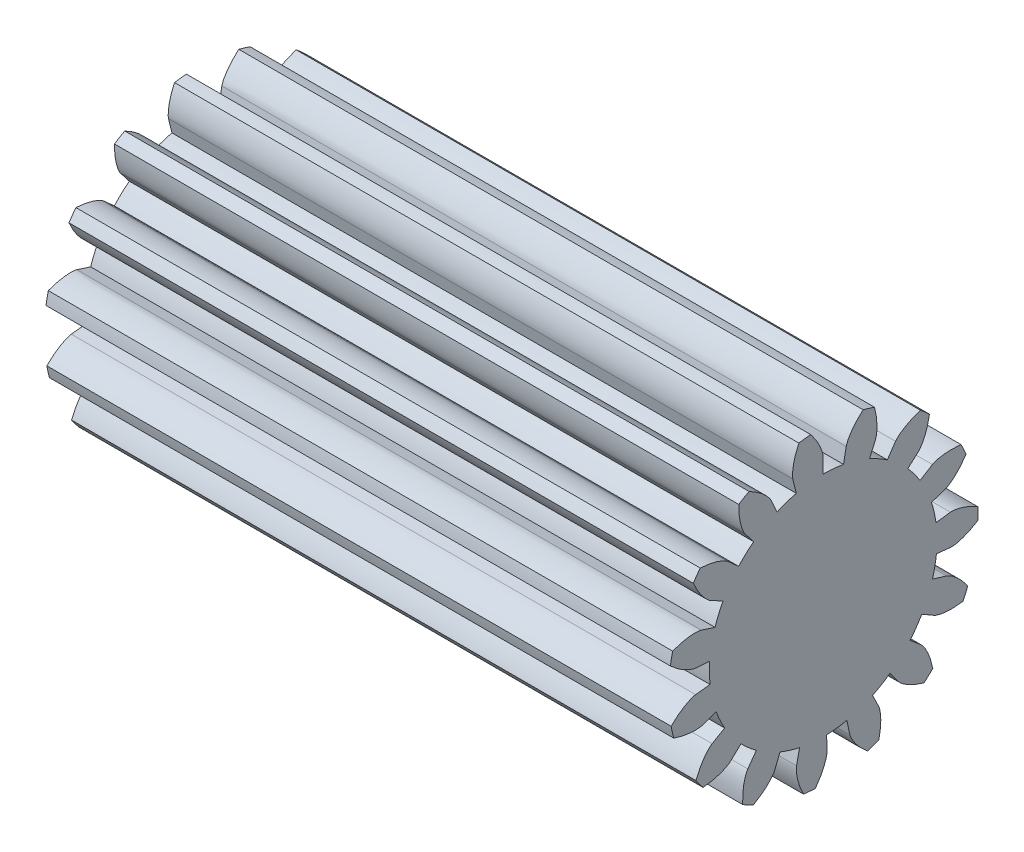
SolidWorks part; units mm, degrees
ref_plane "Front Plane" through (0, 0, 0) normal (1, 0, 0) x (0, 1, 0)
ref_plane "Top Plane" through (0, 0, 0) normal (0, 0, 1) x (0, 1, 0)
ref_plane "Right Plane" through (0, 0, 0) normal (0, 1, 0) x (-1, 0, 0)
sketch "Sketch1" plane through (0, 0, 0) normal (1, 0, 0) x (0, 1, 0)
  circle A0 centre (0, 0) radius 2.8333
  circle A1 centre (0, 0) radius 2.3492 construction
  circle A2 centre (0, 0) radius 2.0833 construction
  circle A3 centre (0, 0) radius 2.5 construction
  dimension "D1" = 5.6667
  dimension "D2" = 4.6985
  dimension "D3" = 4.1667
  dimension "D4" = 5
extrude "Boss-Extrude1" add sketch "Sketch1" along normal blind 11.43
sketch "Sketch3" plane through (11.43, 0, 0) normal (1, 0, 0) x (0, 1, 0)
  line L0 (0, 0) -> (2.3492, 0) construction
  line L1 (0, 0) -> (2.4997, 0.0373) construction
  line L2 (0, 0) -> (2.4899, -0.2242) construction
  line L3 (2.4899, -0.2242) -> (2.3398, -0.2107)
  line L4 (2.4899, -0.2242) -> (3.2461, -0.2923)
  line L5 (3.2461, 0.7075) -> (3.2461, -0.2923)
  line L6 (2.3492, 0) -> (2.0833, 0)
  line L7 (2.3398, -0.2107) -> (2.0749, -0.1869)
  circle A0 centre (0, 0) radius 2.5 construction
  circle A1 centre (0, 0) radius 2.3492 construction
  circle A2 centre (0, 0) radius 2.0833 construction
  arc A3 (2.0833, 0) -> (2.0749, -0.1869) centre (0, 0) cw
  spline S0 degree 4 poles (2.3492, 0) (2.351, 0) (2.3558, 0.0003) (2.3708, 0.0017) (2.4002, 0.0065) (2.436, 0.0154) (2.4766, 0.0283) (2.5151, 0.043) (2.5477, 0.0568) (2.5797, 0.0719) (2.6112, 0.0879) (2.6488, 0.1086) (2.6932, 0.1351) (2.7439, 0.1686) (2.7998, 0.2094) (2.8551, 0.254) (2.908, 0.3003) (2.9597, 0.3497) (3.0083, 0.3994) (3.0568, 0.4536) (3.1005, 0.5049) (3.1472, 0.5652) (3.1841, 0.6146) (3.2302, 0.6825) (3.2566, 0.7234) (3.2865, 0.7723) (3.2993, 0.7944) (3.3072, 0.808) knots 0 0 0 0 0 0.005377 0.015084 0.04661 0.092111 0.119476 0.146842 0.174209 0.201575 0.228941 0.256307 0.307035 0.361767 0.4165 0.471232 0.525964 0.580697 0.635429 0.690161 0.744894 0.799626 0.854358 0.909091 0.954545 1 1 1 1 1 construction
  spline S1 degree 4 poles (2.3492, 0) (2.351, 0) (2.3558, 0.0003) (2.3708, 0.0017) (2.4002, 0.0065) (2.436, 0.0154) (2.4766, 0.0283) (2.5151, 0.043) (2.5477, 0.0568) (2.5797, 0.0719) (2.6112, 0.0879) (2.6488, 0.1086) (2.6932, 0.1351) (2.7439, 0.1686) (2.7998, 0.2094) (2.8551, 0.254) (2.908, 0.3003) (2.9597, 0.3497) (3.0083, 0.3994) (3.0568, 0.4536) (3.1005, 0.5049) (3.1472, 0.5652) (3.1841, 0.6146) (3.2202, 0.6678) (3.2374, 0.694) (3.2461, 0.7075) knots 0 0 0 0 0 0.005377 0.015084 0.04661 0.092111 0.119476 0.146842 0.174209 0.201575 0.228941 0.256307 0.307035 0.361767 0.4165 0.471232 0.525964 0.580697 0.635429 0.690161 0.744894 0.799626 0.854358 0.909091 0.909091 0.909091 0.909091 0.909091
  dimension "D1" = 6
extrude "Cut-Extrude1" cut sketch "Sketch3" against normal through all
mirror "Mirror1" about plane through (0, 2.4899, -0.2242) normal (0, -0.0897, -0.996) of "Cut-Extrude1"
pattern_circular "CirPattern6" count 15 over 360 about axis through (11.43, 0, 0) along (-1, 0, 0) of "Cut-Extrude1", "Mirror1"
equation "\"DiametralPitch\" = 3"
equation "\"NumberTeeth\"= 15"
equation "\"PressureAngle\"= 20"
equation "\"PitchDiameter\"= \"NumberTeeth\" / \"DiametralPitch\""
equation "\"BaseDiameter\"= \"PitchDiameter\" * cos ( \"PressureAngle\" )"
equation "\"Addendum\"= 1 / \"DiametralPitch\""
equation "\"Dedendum\"= 1.25 / \"DiametralPitch\""
equation "\"AddendumDiameter\"= \"PitchDiameter\" + \"Addendum\" + \"Addendum\""
equation "\"DedendumDiameter\"= \"PitchDiameter\" - \"Dedendum\" - \"Dedendum\""
equation "\"ToothSpacing\"= 360 / ( 4 * \"NumberTeeth\" )"
equation "\"D1@Sketch1\"=\"AddendumDiameter\""
equation "\"D2@Sketch1\"=\"BaseDiameter\""
equation "\"D3@Sketch1\"=\"DedendumDiameter\""
equation "\"D4@Sketch1\"=\"PitchDiameter\""
equation "\"D1@Sketch3\"=\"ToothSpacing\""
equation "\"D1@CirPattern6\"=\"NumberTeeth\""
